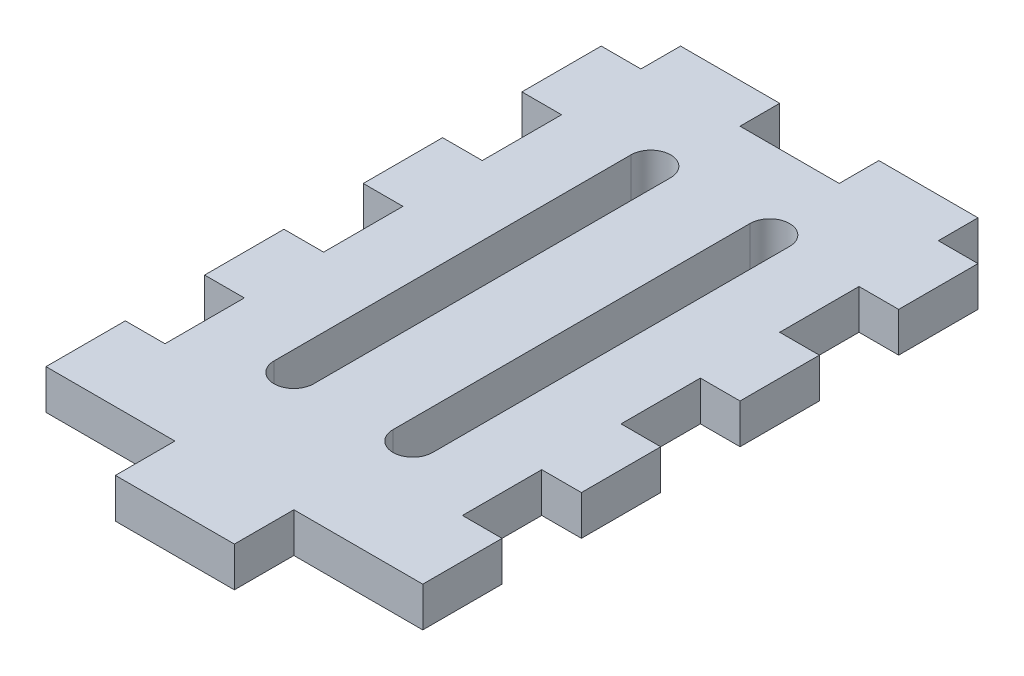
SolidWorks part; units mm, degrees
ref_plane "Front Plane" through (0, 0, 0) normal (0, 0, 1) x (1, 0, 0)
ref_plane "Top Plane" through (0, 0, 0) normal (0, 1, 0) x (1, 0, 0)
ref_plane "Right Plane" through (0, 0, 0) normal (1, 0, 0) x (0, 0, -1)
other "Configuration Table"
sketch "Sketch1" plane through (0, 0, 0) normal (0, 1, 0) x (1, 0, 0)
  line L0 (-8, -18) -> (-8, 18)
  line L5 (-15, 30) -> (15, -30) construction
  line L6 (-15, -30) -> (15, 30) construction
  line L11 (0, 30) -> (0, -30) construction
  line L12 (8, -18) -> (8, 18)
  line L13 (-4, 18) -> (-4, -18)
  line L14 (4, 18) -> (4, -18)
  line L15 (-5, 26) -> (5, 26)
  line L17 (-15, 30) -> (-15, 26)
  line L20 (-15, 30) -> (-5, 30)
  line L21 (-15, 30) -> (-15, 26)
  line L23 (-5, 30) -> (-5, 26)
  line L24 (15, 30) -> (5, 30)
  line L27 (5, 30) -> (5, 26)
  line L28 (-15, -30) -> (-6, -30)
  line L30 (-6, -30) -> (-6, -36)
  line L31 (-6, -36) -> (6, -36)
  line L32 (6, -30) -> (6, -36)
  line L33 (6, -30) -> (15, -30)
  line L34 (-15, -22) -> (-15, -14)
  line L35 (-15, 26) -> (-19, 26)
  line L37 (-15, -30) -> (-19, -30)
  line L39 (-19, 26) -> (-15, 26)
  line L40 (-19, 26) -> (-19, 18)
  line L41 (-19, 18) -> (-15, 18)
  line L43 (-19, 10) -> (-15, 10)
  line L44 (-19, 10) -> (-19, 2)
  line L45 (-19, 2) -> (-15, 2)
  line L47 (-19, -6) -> (-15, -6)
  line L48 (-19, -6) -> (-19, -14)
  line L49 (-19, -14) -> (-15, -14)
  line L51 (-15, -30) -> (-19, -30)
  line L53 (-15, -22) -> (-19, -22)
  line L54 (-19, -30) -> (-19, -22)
  line L55 (-15, -6) -> (-15, 2)
  line L56 (-15, 10) -> (-15, 18)
  line L57 (15, -30) -> (19, -30)
  line L58 (19, -30) -> (19, -22)
  line L59 (15, -22) -> (19, -22)
  line L60 (15, -22) -> (15, -14)
  line L61 (19, -14) -> (15, -14)
  line L62 (19, -6) -> (19, -14)
  line L63 (19, -6) -> (15, -6)
  line L64 (15, -6) -> (15, 2)
  line L65 (19, 2) -> (15, 2)
  line L66 (19, 10) -> (19, 2)
  line L67 (19, 10) -> (15, 10)
  line L68 (15, 10) -> (15, 18)
  line L69 (19, 18) -> (15, 18)
  line L70 (19, 26) -> (19, 18)
  line L71 (15, 26) -> (19, 26)
  line L72 (15, 30) -> (15, 26)
  arc A0 (-8, 18) -> (-4, 18) centre (-6, 18) cw
  arc A1 (-8, -18) -> (-4, -18) centre (-6, -18) ccw
  arc A2 (8, 18) -> (4, 18) centre (6, 18) ccw
  arc A3 (8, -18) -> (4, -18) centre (6, -18) cw
  point P0 (0, 0)
  point P6 (0, 0)
  point P47 (-17, 2)
  dimension "D5" = 10
  dimension "D1" = 60
  dimension "D2" = 30
  dimension "D3" = 6
  dimension "D4" = 36
  dimension "D6" = 10
  dimension "D7" = 4
  dimension "D8" = 6
  dimension "D9" = 4
  dimension "D10" = 8
  dimension "D11" = 10
  dimension "D12" = 8
  dimension "D13" = 8
  dimension "D14" = 8
  dimension "D15" = 8
  dimension "D16" = 8
  dimension "D17" = 8
  dimension "D18" = 4
  dimension "D19" = 12
extrude "Boss-Extrude1" add sketch "Sketch1" along normal blind 4 contours L72 L24 L27 L15 L23 L20 L17 L35 L40 L41 L56 L43 L44 L45 L55 L47 L48 L49 L34 L53 L54 L37 L28 L30 L31 L32 L33 L57 L58 L59 L60 L61 L62 L63 L64 L65 L66 L67 L68 L69 L70 L71 A1 L0 A0 L13 L12 A3 L14
